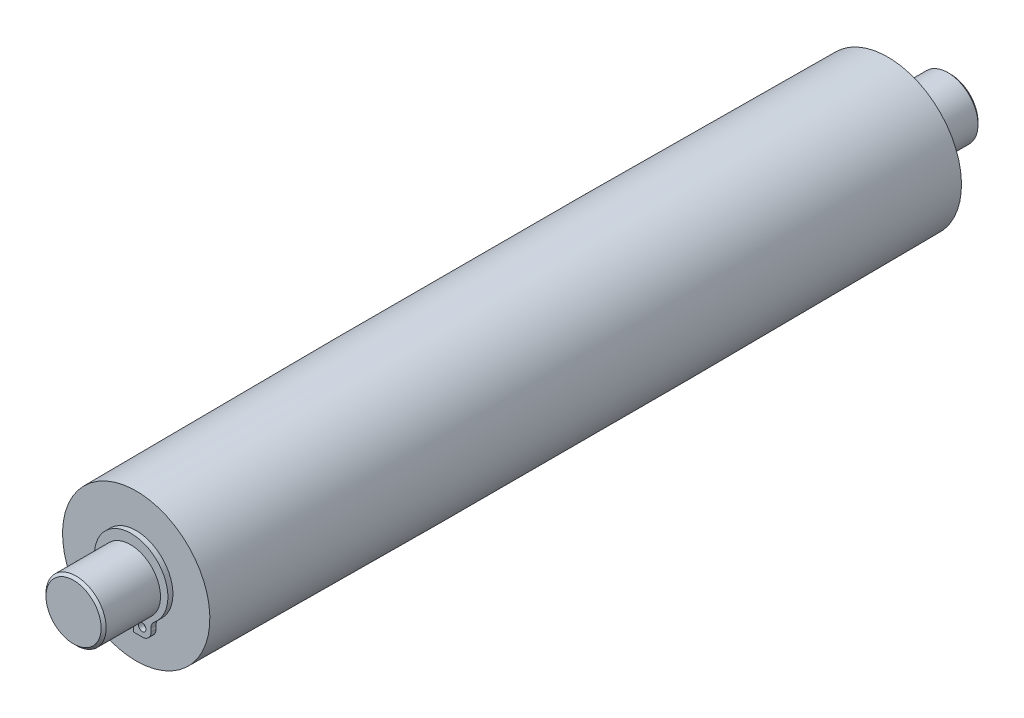
SolidWorks part; units mm, degrees
ref_plane "Front Plane" through (0, 0, 0) normal (0, 0, 1) x (1, 0, 0)
ref_plane "Top Plane" through (0, 0, 0) normal (0, 1, 0) x (1, 0, 0)
ref_plane "Right Plane" through (0, 0, 0) normal (1, 0, 0) x (0, 0, -1)
sketch "Sketch1" plane through (0, 0, 0) normal (1, 0, 0) x (0, 0, -1)
  line L1 (-75, 14.7) -> (-75, 0) construction
  line L4 (87.5, 15) -> (87.5, 0) construction
  line L5 (87.5, 6) -> (76.15, 6)
  line L6 (76.15, 6) -> (76.15, 5.75)
  line L7 (76.15, 5.75) -> (75, 5.75)
  line L8 (75, 14.7) -> (75, 0) construction
  line L9 (-87.5, 0) -> (87.5, 0)
  line L10 (75, 5.75) -> (75, 14.7)
  line L11 (-75, 14.7) -> (-75, 5.75)
  line L12 (-87.5, 0) -> (-87.5, 15) construction
  line L13 (-87.5, 6) -> (-87.5, 0)
  line L14 (-75, 5.75) -> (-76.15, 5.75)
  line L15 (-76.15, 5.75) -> (-76.15, 6)
  line L16 (-76.15, 6) -> (-87.5, 6)
  line L20 (0, 0) -> (0, 15) construction
  line L21 (87.5, 6) -> (87.5, 0)
  line L78 (-87.5, 0) -> (87.5, 0) construction
  arc A0 (75, 14.7) -> (-75, 14.7) centre (0, -9360.15) ccw
  dimension "B" = 150
  dimension "FIX_2" = 30
  dimension "FIX_3" = 11.5
  dimension "FIX_4" = 12
  dimension "FIX_1" = 1.15
  dimension "FIX_5" = 12.5
  dimension "FIX_6" = 12.5
  dimension "FIX_7" = 0.3
revolve "Revolve1" add sketch "Sketch1" angle 360 about L78
sketch "Sketch2" plane through (0, 0, 75) normal (0, 0, 1) x (1, 0, 0)
  line L6 (16.5, 0) -> (-16.5, 0) construction
  line L7 (-0.45, -8.95) -> (-0.45, -5.7324)
  line L8 (0, 0) -> (0, -8.95) construction
  line L9 (-7.3062, 0) -> (7.3062, 0) construction
  line L10 (0.45, -5.7324) -> (0.45, -8.95)
  line L11 (0.45, -8.95) -> (2.25, -8.95)
  line L12 (3.95, -7.25) -> (3.95, -6.5126)
  line L13 (-3.95, -6.5126) -> (-3.95, -7.25)
  line L14 (-2.25, -8.95) -> (-0.45, -8.95)
  arc A0 (0.45, -5.7324) -> (-0.45, -5.7324) centre (0, 0) ccw
  circle A6 centre (-2.2, -7.25) radius 0.75
  circle A9 centre (2.2, -7.25) radius 0.75
  arc A11 (2.25, -8.95) -> (3.95, -7.25) centre (2.25, -7.25) ccw
  arc A12 (4.5857, -5.187) -> (3.95, -6.5126) centre (5.65, -6.5126) ccw
  arc A13 (4.5857, -5.187) -> (-4.5857, -5.187) centre (0, 0.525) ccw
  arc A14 (-3.95, -6.5126) -> (-4.5857, -5.187) centre (-5.65, -6.5126) ccw
  arc A15 (-3.95, -7.25) -> (-2.25, -8.95) centre (-2.25, -7.25) ccw
  dimension "FIX_11" = 8.95
  dimension "FIX_15" = 1.5
  dimension "FIX_16" = 1.7
  dimension "FIX_9" = 14.65
  dimension "FIX_17" = 1.7
  dimension "FIX_12" = 0.9
  dimension "FIX_13" = 4.4
  dimension "FIX_14" = 1.7
  dimension "FIX_18" = 0.525
  dimension "FIX_10" = 7.9
extrude "Boss-Extrude1" add sketch "Sketch2" along normal blind 1
mirror "Mirror1" about plane through (0, 0, 0) normal (0, 0, 1) of "Boss-Extrude1"
chamfer "Chamfer1" distance 0.5 2 edges at (0, -6, -87.5) (0, -6, 87.5)
ref_plane "Plane1" through (0, 0, 87.5) normal (0, 0, 1) x (1, 0, 0)
ref_plane "Plane2" through (0, 0, -87.5) normal (0, 0, 1) x (1, 0, 0)
